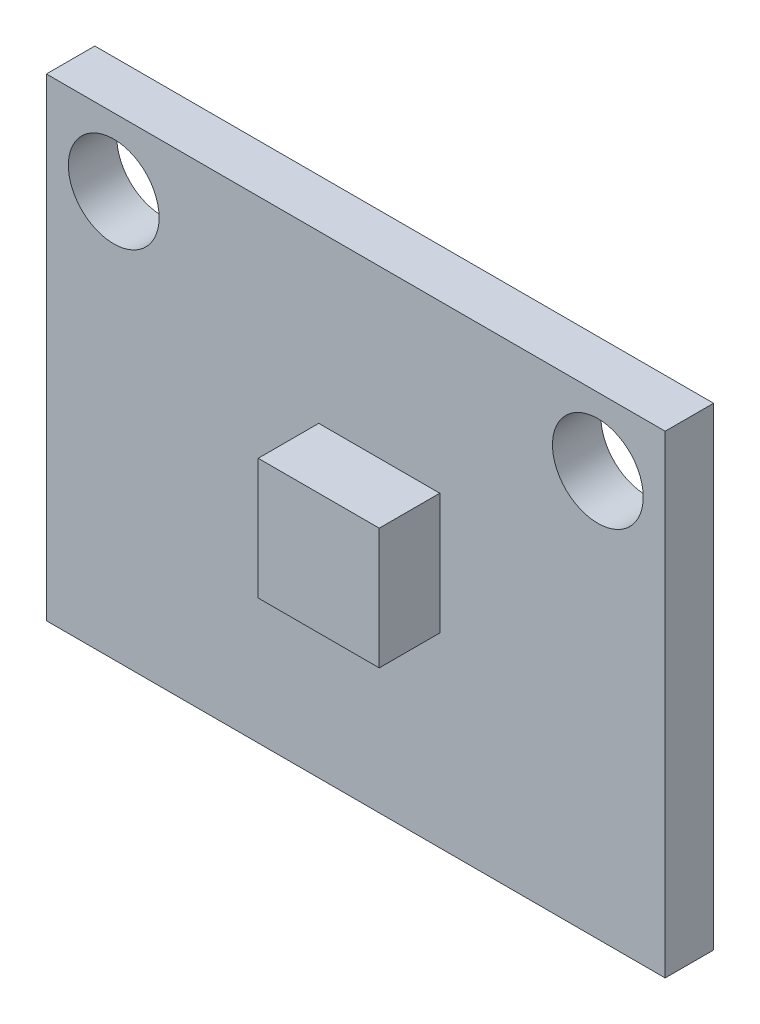
SolidWorks part; units mm, degrees
ref_plane "Přední rovina" through (0, 0, 0) normal (0, 0, 1) x (1, 0, 0)
ref_plane "Horní rovina" through (0, 0, 0) normal (0, 1, 0) x (1, 0, 0)
ref_plane "Pravá rovina" through (0, 0, 0) normal (1, 0, 0) x (0, 0, -1)
sketch "Skica1" plane through (0, 0, 0) normal (0, 0, 1) x (1, 0, 0)
  line L0 (-8, 5.575) -> (8, 5.575) construction
  line L1 (-10.225, -7.825) -> (10.225, -7.825)
  line L2 (-10.225, -7.825) -> (-10.225, 7.825)
  line L3 (-10.225, 7.825) -> (10.225, 7.825)
  line L4 (10.225, -7.825) -> (10.225, 7.825)
  line L5 (-10.225, -7.825) -> (10.225, 7.825) construction
  line L6 (-10.225, 7.825) -> (10.225, -7.825) construction
  circle A0 centre (-8, 5.575) radius 1.5
  circle A1 centre (8, 5.575) radius 1.5
  point P0 (0, 0)
  point P8 (0, 7.825)
  point P12 (0, 5.575)
  dimension "D5" = 3
  dimension "D1" = 20.45
  dimension "D2" = 15.65
  dimension "D3" = 2.25
  dimension "D4" = 16
extrude "Přidat vysunutím1" add sketch "Skica1" along normal blind 1.6
sketch "Skica2" plane through (0, 0, 1.6) normal (0, 0, 1) x (1, 0, 0)
  line L0 (10.225, 7.825) -> (-10.225, 7.825) construction
  line L1 (2.775, 2.325) -> (-1.225, 2.325)
  line L2 (2.775, 2.325) -> (2.775, -1.675)
  line L3 (2.775, -1.675) -> (-1.225, -1.675)
  line L4 (-1.225, 2.325) -> (-1.225, -1.675)
  line L5 (2.775, 2.325) -> (-1.225, -1.675) construction
  line L6 (2.775, -1.675) -> (-1.225, 2.325) construction
  line L7 (-10.225, 7.825) -> (-10.225, -7.825) construction
  point P0 (0.775, 0.325)
  dimension "D1" = 7.5
  dimension "D2" = 11
  dimension "D3" = 4
  dimension "D4" = 4
extrude "Přidat vysunutím2" add sketch "Skica2" along normal blind 2 separate body
ref_plane "Rovina1" through (0, 0, 7) normal (0, 0, -1) x (-1, 0, 0)
sketch "Skica3" plane through (0, 0, 7) normal (0, 0, 1) x (1, 0, 0)
  line L0 (4.775, -37.175) -> (10.225, -37.175)
  line L1 (-10.225, -22.175) -> (-10.225, -7.825)
  line L2 (-10.225, -7.825) -> (-8.225, -7.825)
  line L3 (-8.225, -7.825) -> (-8.225, -22.175)
  line L4 (4.775, -35.175) -> (10.225, -35.175)
  line L5 (10.225, -35.175) -> (10.225, -37.175)
  line L6 (10.225, 7.825) -> (-10.225, 7.825) construction
  line L9 (-10.225, -7.825) -> (10.225, -7.825) construction
  line L10 (-10.225, 7.825) -> (-10.225, -7.825) construction
  line L11 (10.225, -7.825) -> (10.225, 7.825) construction
  arc A0 (-10.225, -22.175) -> (4.775, -37.175) centre (4.775, -22.175) ccw
  arc A1 (-8.225, -22.175) -> (4.775, -35.175) centre (4.775, -22.175) ccw
  dimension "D1" = 2
  dimension "D2" = 45
  dimension "D3" = 30
extrude "Přidat vysunutím3" [suppressed] add sketch "Skica3" against normal blind 2 separate body contours A0 L0 L5 L4 A1 L3 L2 L1
